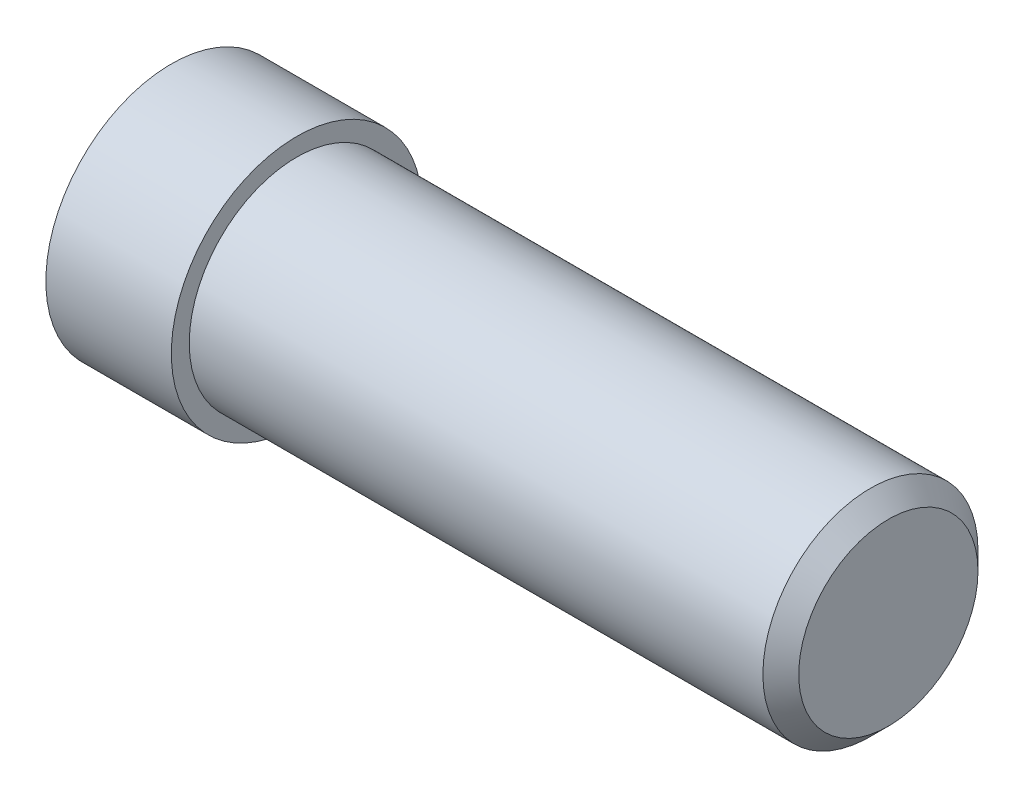
SolidWorks part; units mm, degrees
ref_plane "Front Plane" through (0, 0, 0) normal (0, 0, 1) x (1, 0, 0)
ref_plane "Top Plane" through (0, 0, 0) normal (0, 1, 0) x (1, 0, 0)
ref_plane "Right Plane" through (0, 0, 0) normal (1, 0, 0) x (0, 0, -1)
sketch "Sketch1" plane through (0, 0, 0) normal (0, 1, 0) x (1, 0, 0)
  line L0 (0, 0) -> (-1016, 0)
  line L1 (-1016, 0) -> (-1016, 177.8)
  line L2 (-1016, 177.8) -> (-838.2, 177.8)
  line L3 (-838.2, 177.8) -> (-838.2, 152.4)
  line L4 (-838.2, 152.4) -> (0, 152.4)
  line L5 (0, 152.4) -> (0, 0)
  dimension "D1" = 177.8
  dimension "D2" = 177.8
  dimension "D3" = 838.2
  dimension "D4" = 152.4
revolve "Revolve1" add sketch "Sketch1" angle 360 about L0
chamfer "Chamfer1" distance 25.4 angle 45 1 edges at (0, 0, -152.4)
